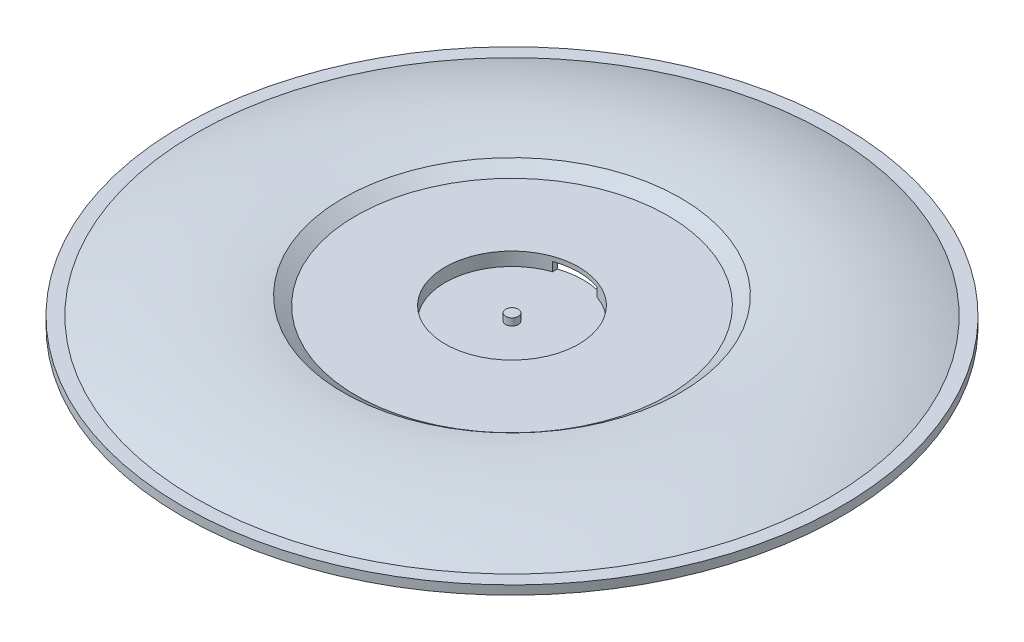
SolidWorks part; units mm, degrees
ref_plane "Front Plane" through (0, 0, 0) normal (0, 0, 1) x (1, 0, 0)
ref_plane "Top Plane" through (0, 0, 0) normal (0, 1, 0) x (1, 0, 0)
ref_plane "Right Plane" through (0, 0, 0) normal (1, 0, 0) x (0, 0, -1)
sketch "Sketch1" plane through (0, 0, 0) normal (0, 0, 1) x (1, 0, 0)
  line L0 (0, 0) -> (0, 14.5222) construction
  line L1 (0, 0.5) -> (7.5, 0.5)
  line L2 (7.5, 0.5) -> (7.5, 2)
  line L3 (7.5, 2) -> (17.5, 2)
  line L4 (17.5, 2) -> (18.9281, 3)
  line L5 (18.9281, 3) -> (35.5, 1) construction
  line L6 (35.5, 1) -> (37, 1)
  line L7 (37, 1) -> (37, 0)
  line L8 (0, 0) -> (8, 0)
  line L9 (8, 0) -> (8, 1.5)
  line L10 (8, 1.5) -> (17.6576, 1.5)
  line L11 (17.6576, 1.5) -> (19.1153, 2.5207)
  line L12 (35.4046, 0.5) -> (36.5, 0.5)
  line L13 (36.5, 0.5) -> (36.5, 0)
  line L14 (0, 0.5) -> (0, 0)
  line L15 (37, 0) -> (36.5, 0)
  arc A0 (18.9281, 3) -> (35.5, 1) centre (23.3887, -29.6972) cw
  arc A1 (19.1153, 2.5207) -> (35.4046, 0.5) centre (23.3887, -29.6972) cw
  dimension "D10" = 33
  dimension "D1" = 0.5
  dimension "D2" = 1.5
  dimension "D3" = 15
  dimension "D4" = 74
  dimension "D5" = 1
  dimension "D6" = 1.5
  dimension "D7" = 3
  dimension "D8" = 145
  dimension "D9" = 35
  dimension "D11" = 0.5
revolve "Revolve1" add sketch "Sketch1" angle 360 about L0
sketch "Sketch2" plane through (0, 0, 0) normal (0, 0, 1) x (1, 0, 0)
  line L1 (-2.5, 0.5) -> (2.5, 0.5)
  line L2 (-2.5, 0.5) -> (-2.5, 1.5)
  line L3 (-2.5, 1.5) -> (2.5, 1.5)
  line L4 (2.5, 0.5) -> (2.5, 1.5)
  line L5 (-2.5, 0.5) -> (2.5, 1.5) construction
  line L6 (-2.5, 1.5) -> (2.5, 0.5) construction
  point P0 (0, 1)
  dimension "D2" = 1
  dimension "D3" = 5
extrude "Cut-Extrude1" cut sketch "Sketch2" against normal mid plane 30
sketch "Sketch3" plane through (0, 0, 0) normal (0, 0, 1) x (1, 0, 0)
  line L0 (2.5, 0.5) -> (-2.5, 0.5) construction
  line L1 (0, 0.5) -> (0.7, 0.5)
  line L2 (0, 0.5) -> (0, 1.3)
  line L3 (0, 1.3) -> (0.7, 1.3)
  line L4 (0.7, 0.5) -> (0.7, 1.3)
  dimension "D1" = 0.7
  dimension "D2" = 0.8
revolve "Revolve2" add sketch "Sketch3" angle 360 about L2
